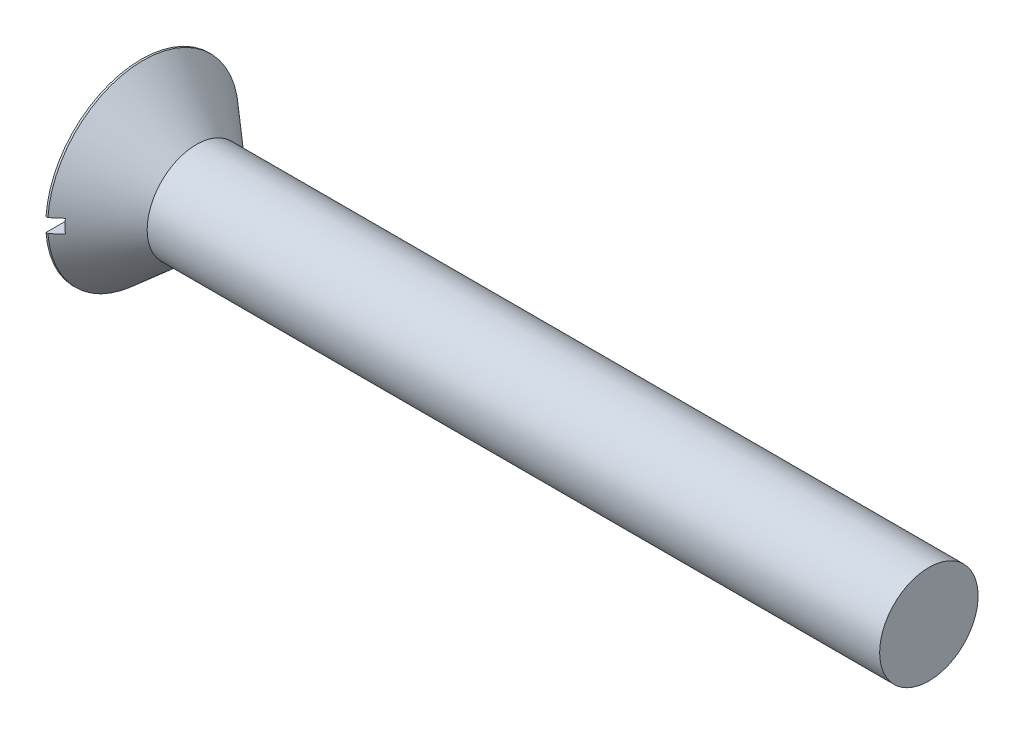
SolidWorks part; units mm, degrees
revolve "Base-Revolve" add sketch "BodySke" angle 360 about L5
sketch "BodySke" plane through (0, 0, 0) normal (0, 0, 1) x (1, 0, 0)
  line L0 (0, 0) -> (0, 12.319)
  line L1 (0, 12.319) -> (0.2455, 12.319)
  line L2 (7.112, 6.35) -> (101.6, 6.35)
  line L3 (101.6, 6.35) -> (101.6, 0)
  line L4 (101.6, 0) -> (0, 0)
  line L5 (-6.35, 0) -> (82.55, 0) construction
  line L6 (7.112, -6.35) -> (101.6, -6.35) construction
  line L7 (0.2455, -12.319) -> (7.112, -6.35) construction
  line L8 (0.2455, 12.319) -> (7.112, 6.35)
  line L9 (0, -12.319) -> (0.2455, -12.319) construction
  line L10 (8.382, 7.9375) -> (8.382, -1.5875) construction
  line L11 (82.55, 6.35) -> (82.55, -3.175) construction
  dimension "Diameter" = 12.7
  dimension "Length" = 101.6
  dimension "Head_ht" = 7.112
  dimension "Head_dia" = 24.638
  dimension "Head_ang" = 82
  dimension "D6" = 0.2455
  dimension "Advance" = 1.27
  dimension "Thread_nom" = 19.05
cosmetic thread "ThreadCosmetic" [suppressed] parameters "Thread_length"=19.05, "Thread_minor"=4.8387
extrude "Slot" cut sketch "Sketch6" against normal blind 1.4478
sketch "Sketch6" plane through (0, 0, 0) normal (-1, 0, 0) x (0, 0, 1)
  line L0 (-12.319, -0.889) -> (12.319, -0.889)
  line L1 (-12.319, -0.889) -> (-12.319, 0.889)
  line L2 (12.319, 0.889) -> (-12.319, 0.889)
  line L3 (12.319, 0.889) -> (12.319, -0.889)
  dimension "Slot_width" = 1.778
  dimension "D1" = 0.889
  dimension "D2" = 24.638
  dimension "D3" = 12.319
ref_plane "Plane1" through (0, 0, 0) normal (0, 0, 1) x (1, 0, 0)
ref_plane "Plane2" through (0, 0, 0) normal (0, 1, 0) x (1, 0, 0)
ref_plane "Plane3" through (0, 0, 0) normal (1, 0, 0) x (0, 0, -1)
sketch "ThdSchSke" plane through (0, 0, 0) normal (0, 0, 1) x (1, 0, 0)
  line L0 (82.55, -2.4193) -> (79.7978, -6.35)
  line L1 (82.55, -2.4193) -> (85.3023, -6.35)
  line L2 (85.3023, -6.35) -> (85.3023, -7.9375)
  line L3 (-3.175, 0) -> (5.1513, 0) construction
  line L5 (85.3023, -7.9375) -> (79.7978, -7.9375)
  line L6 (79.7978, -7.9375) -> (79.7978, -6.35)
  line L7 (0, 12.319) -> (0, 0.889) construction
  dimension "Diameter" = 12.7
  dimension "Thread_minor" = 4.8387
  dimension "Start" = 82.55
revolve "ThreadSchematic" [suppressed] cut sketch "ThdSchSke" angle 360 about L3
pattern_linear "ThdSchPat" [suppressed]
equation "\"D1@Sketch6\" = \"Slot_width@Sketch6\" / 2"
equation "\"D2@Sketch6\" = \"Head_dia@BodySke\""
equation "\"D3@Sketch6\" = \"D2@Sketch6\" / 2"
equation "\"Thread_length@ThreadCosmetic\" = ((sgn( (\"Length@BodySke\" - \"Advance@BodySke\" - \"Head_ht@BodySke\" ) - \"Thread_nom@BodySke\" )-1)*( (\"Length@BodySke\" - \"Advance@BodySke\" - \"Head_ht@BodySke\" ) - \"Thread_nom@BodySke\" ))/-2+ \"Thread_nom@BodySke\""
equation "\"Thread_minor@ThdSchSke\" = \"Thread_minor@ThreadCosmetic\""
equation "\"Diameter@ThdSchSke\" = \"Diameter@BodySke\""
equation "\"Overcut@ThdSchSke\" = \"Diameter@BodySke\" * 1.25"
equation "\"Start@ThdSchSke\" = 0.000001 + \"Length@BodySke\" - \"Thread_length@ThreadCosmetic\"  '---Countersunk---"
equation "\"Num_threads@ThdSchPat\" = int( \"Thread_length@ThreadCosmetic\" / \"Advance@BodySke\" + 0.999 )  + 1"
equation "\"Advance@ThdSchPat\" = \"Thread_length@ThreadCosmetic\" /  (\"Num_threads@ThdSchPat\" - 1) 'relax it"
